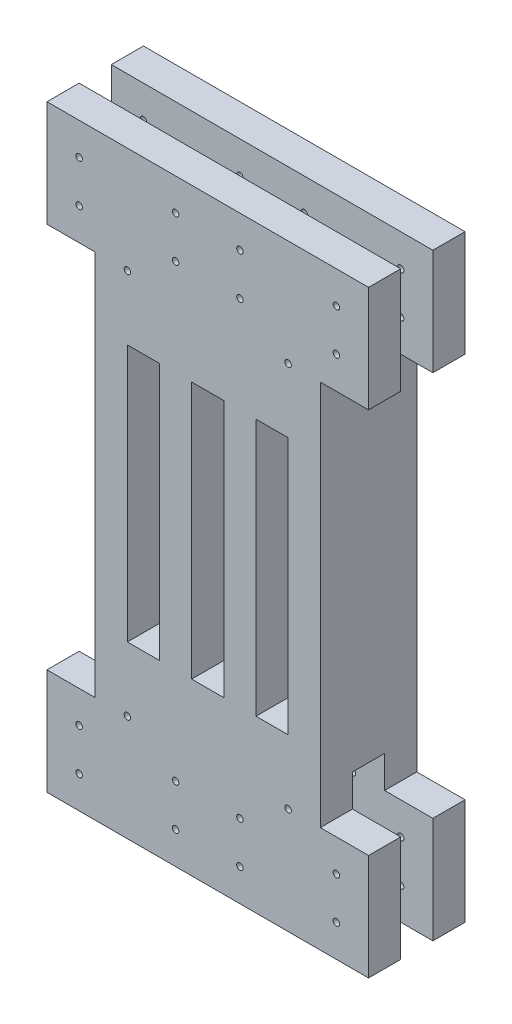
SolidWorks part; units mm, degrees
ref_plane "Plan de face" through (0, 0, 0) normal (0, 0, 1) x (1, 0, 0)
ref_plane "Plan de dessus" through (0, 0, 0) normal (0, 1, 0) x (1, 0, 0)
ref_plane "Plan de droite" through (0, 0, 0) normal (1, 0, 0) x (0, 0, -1)
sketch "Esquisse1" plane through (0, 0, -20) normal (0, 0, 1) x (1, 0, 0)
  line L0 (-136.1414, 52.5358) -> (-136.1414, 19.5358)
  line L1 (-136.1414, 52.5358) -> (-36.1414, 52.5358)
  line L2 (-136.1414, 19.5358) -> (-36.1414, 19.5358)
  line L3 (-36.1414, 52.5358) -> (-36.1414, 19.5358)
  line L4 (-136.1414, -100.4642) -> (-136.1414, -133.4642)
  line L5 (-136.1414, -100.4642) -> (-36.1414, -100.4642)
  line L6 (-136.1414, -133.4642) -> (-36.1414, -133.4642)
  line L7 (-36.1414, -100.4642) -> (-36.1414, -133.4642)
  line L8 (-121.1414, 19.5358) -> (-51.1414, 19.5358)
  line L9 (-121.1414, 19.5358) -> (-121.1414, -100.4642)
  line L10 (-51.1414, 19.5358) -> (-51.1414, -100.4642)
  line L11 (-121.1414, -100.4642) -> (-51.1414, -100.4642)
  line L12 (-173.1414, 52.5358) -> (-166.1414, 52.5358) construction
  line L15 (-161.1414, -100.4642) -> (-171.1414, -100.4642) construction
  line L16 (-173.1414, -133.4642) -> (-166.1414, -133.4642) construction
  line L17 (-171.1414, 19.5358) -> (-161.1414, 19.5358) construction
  line L18 (-21.1414, 9.5358) -> (-21.1414, 59.5358) construction
  line L19 (-151.1414, 9.5358) -> (-151.1414, 59.5358) construction
  line L20 (-21.1414, -90.4642) -> (-21.1414, -140.4642) construction
  line L21 (-61.1414, -80.4642) -> (-61.1414, -0.4642)
  line L22 (-61.1414, -80.4642) -> (-71.1414, -80.4642)
  line L23 (-61.1414, -0.4642) -> (-71.1414, -0.4642)
  line L24 (-71.1414, -80.4642) -> (-71.1414, -0.4642)
  line L25 (-81.1414, -80.4642) -> (-81.1414, -0.4642)
  line L26 (-81.1414, -80.4642) -> (-91.1414, -80.4642)
  line L27 (-81.1414, -0.4642) -> (-91.1414, -0.4642)
  line L28 (-91.1414, -80.4642) -> (-91.1414, -0.4642)
  line L29 (-101.1414, -80.4642) -> (-101.1414, -0.4642)
  line L30 (-101.1414, -80.4642) -> (-111.1414, -80.4642)
  line L31 (-101.1414, -0.4642) -> (-111.1414, -0.4642)
  line L32 (-111.1414, -80.4642) -> (-111.1414, -0.4642)
  line L33 (-86.1414, -90.4642) -> (-21.1414, -90.4642) construction
  line L34 (63.8586, 9.5358) -> (-86.1414, 9.5358) construction
  line L36 (-86.1414, -90.4642) -> (-86.1414, -80.4642) construction
  line L37 (-86.1414, -90.4642) -> (-86.1414, -140.4642) construction
  line L38 (-86.1414, 9.5358) -> (-86.1414, 59.5358) construction
  line L39 (-86.1414, -140.4642) -> (-86.1414, -90.4642) construction
  circle A0 centre (-126.1414, 42.5358) radius 1
  circle A1 centre (-126.1414, 29.5358) radius 1
  circle A2 centre (-111.1414, 19.5358) radius 1
  circle A3 centre (-61.1414, 19.5358) radius 1
  circle A4 centre (-46.1414, 29.5358) radius 1
  circle A5 centre (-46.1414, 42.5358) radius 1
  circle A6 centre (-96.1414, 42.5358) radius 1
  circle A7 centre (-96.1414, 29.5358) radius 1
  circle A8 centre (-76.1414, 42.5358) radius 1
  circle A9 centre (-76.1414, 29.5358) radius 1
  circle A10 centre (-126.1414, -110.4642) radius 1
  circle A11 centre (-96.1414, -110.4642) radius 1
  circle A12 centre (-96.1414, -123.4642) radius 1
  circle A13 centre (-126.1414, -123.4642) radius 1
  circle A14 centre (-111.1414, -100.4642) radius 1
  circle A15 centre (-61.1414, -100.4642) radius 1
  circle A16 centre (-76.1414, -110.4642) radius 1
  circle A17 centre (-76.1414, -123.4642) radius 1
  circle A18 centre (-46.1414, -110.4642) radius 1
  circle A19 centre (-46.1414, -123.4642) radius 1
  dimension "D15" = 2
  dimension "D16" = 2
  dimension "D22" = 2
  dimension "D23" = 2
  dimension "D24" = 2
  dimension "D34" = 2
  dimension "D35" = 2
  dimension "D36" = 2
  dimension "D37" = 2
  dimension "D38" = 2
  dimension "D47" = 2
  dimension "D48" = 2
  dimension "D49" = 2
  dimension "D50" = 2
  dimension "D51" = 2
  dimension "D52" = 2
  dimension "D61" = 2
  dimension "D62" = 2
  dimension "D63" = 2
  dimension "D64" = 2
  dimension "D1" = 15
  dimension "D2" = 15
  dimension "D3" = 15
  dimension "D4" = 15
  dimension "D5" = 15
  dimension "D6" = 10
  dimension "D7" = 10
  dimension "D8" = 10
  dimension "D9" = 10
  dimension "D10" = 10
  dimension "D11" = 10
  dimension "D12" = 10
  dimension "D13" = 10
  dimension "D14" = 10
  dimension "D17" = 10
  dimension "D18" = 10
  dimension "D19" = 10
  dimension "D20" = 10
  dimension "D21" = 10
  dimension "D25" = 10
  dimension "D26" = 10
  dimension "D27" = 10
  dimension "D28" = 10
  dimension "D29" = 10
  dimension "D30" = 10
  dimension "D31" = 10
  dimension "D32" = 10
  dimension "D33" = 10
  dimension "D39" = 10
  dimension "D40" = 10
  dimension "D41" = 10
  dimension "D42" = 10
  dimension "D43" = 10
  dimension "D44" = 10
  dimension "D45" = 10
  dimension "D46" = 10
  dimension "D53" = 10
  dimension "D54" = 10
  dimension "D55" = 10
  dimension "D56" = 10
  dimension "D57" = 10
  dimension "D58" = 10
  dimension "D59" = 10
  dimension "D60" = 10
  dimension "D65" = 10
  dimension "D66" = 10
extrude "Boss.-Extru.1" add sketch "Esquisse1" along normal blind 10 and the other way blind 20
sketch "Esquisse3" plane through (0, 0, -40) normal (0, 0, -1) x (-1, 0, 0)
  line L0 (36.1414, -133.4642) -> (136.1414, -133.4642)
  line L1 (36.1414, -133.4642) -> (36.1414, -90.4642)
  line L2 (136.1414, -133.4642) -> (136.1414, -90.4642)
  line L3 (36.1414, -90.4642) -> (136.1414, -90.4642)
  line L4 (136.1414, 52.5358) -> (36.1414, 52.5358)
  line L5 (136.1414, 52.5358) -> (136.1414, 9.5358)
  line L6 (36.1414, 52.5358) -> (36.1414, 9.5358)
  line L7 (136.1414, 9.5358) -> (36.1414, 9.5358)
  line L8 (-63.8586, 9.5358) -> (86.1414, 9.5358) construction
  line L9 (236.1414, -90.4642) -> (86.1414, -90.4642) construction
extrude "Enlèv. mat.-Extru.1" cut sketch "Esquisse3" against normal blind 10 from offset 10
